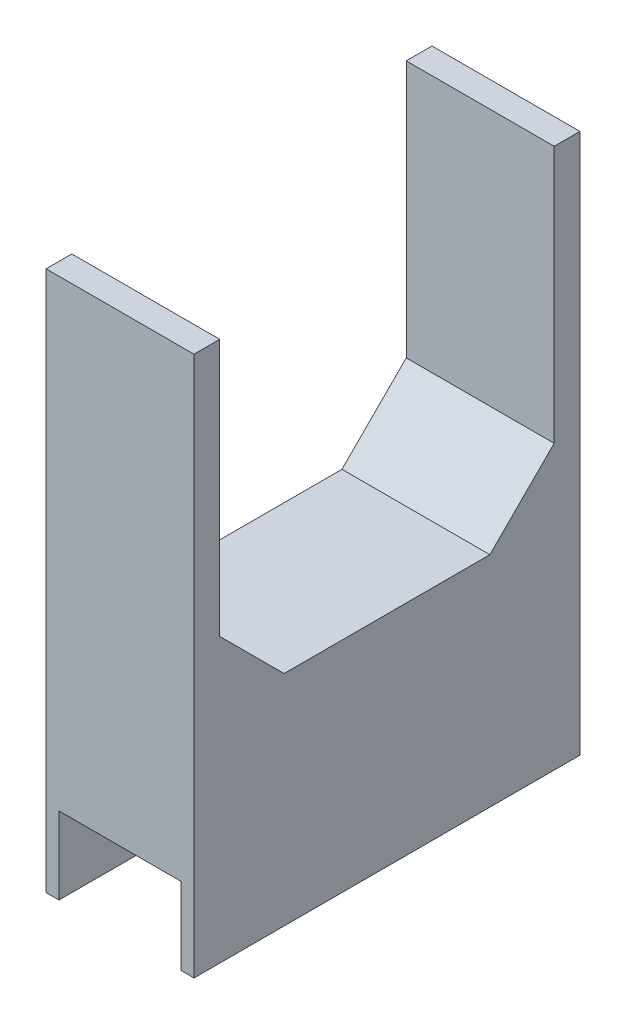
SolidWorks part; units mm, degrees
ref_plane "Front Plane" through (0, 0, 0) normal (0, 0, 1) x (1, 0, 0)
ref_plane "Top Plane" through (0, 0, 0) normal (0, 1, 0) x (1, 0, 0)
ref_plane "Right Plane" through (0, 0, 0) normal (1, 0, 0) x (0, 0, -1)
sketch "Sketch1" plane through (0, 0, 0) normal (0, 1, 0) x (1, 0, 0)
  line L1 (-5.75, -15) -> (5.75, -15)
  line L2 (-5.75, -15) -> (-5.75, 15)
  line L3 (-5.75, 15) -> (5.75, 15)
  line L4 (5.75, -15) -> (5.75, 15)
  line L5 (-5.75, -15) -> (5.75, 15) construction
  line L6 (-5.75, 15) -> (5.75, -15) construction
  point P0 (0, 0)
  dimension "D1" = 30
  dimension "D2" = 11.5
extrude "Boss-Extrude1" add sketch "Sketch1" along normal blind 11
sketch "Sketch3" plane through (0, 0, 0) normal (0, -1, 0) x (1, 0, 0)
  line L1 (-5.75, -15) -> (5.75, -15)
  line L2 (-5.75, -15) -> (-5.75, 15)
  line L3 (-5.75, 15) -> (5.75, 15)
  line L4 (5.75, -15) -> (5.75, 15)
  line L5 (-5.75, -15) -> (5.75, 15) construction
  line L6 (-5.75, 15) -> (5.75, -15) construction
  point P0 (0, 0)
extrude "Boss-Extrude3" add sketch "Sketch3" along normal blind 6
sketch "Sketch4" plane through (0, 0, 15) normal (0, 0, 1) x (1, 0, 0)
  line L0 (5.75, -6) -> (-5.75, -6) construction
  line L1 (-4.75, -6) -> (4.75, -6)
  line L2 (-4.75, -6) -> (-4.75, 0)
  line L3 (-4.75, 0) -> (4.75, 0)
  line L4 (4.75, -6) -> (4.75, 0)
  line L5 (-5.75, 11) -> (-5.75, -6) construction
  line L6 (5.75, 11) -> (5.75, -6) construction
  dimension "D1" = 1
  dimension "D2" = 1
  dimension "D3" = 6
extrude "Cut-Extrude1" cut sketch "Sketch4" against normal through all
sketch "Sketch7" plane through (0, 0, 0) normal (0, -1, 0) x (1, 0, 0)
  line L1 (-1, -3) -> (1, -3)
  line L2 (-1, -3) -> (-1, 3)
  line L3 (-1, 3) -> (1, 3)
  line L4 (1, -3) -> (1, 3)
  line L5 (-1, -3) -> (1, 3) construction
  line L6 (-1, 3) -> (1, -3) construction
  point P0 (0, 0)
  dimension "D1" = 2
  dimension "D2" = 6
extrude "Cut-Extrude2" cut sketch "Sketch7" against normal blind 10
sketch "Sketch8" plane through (0, 11, 0) normal (0, 1, 0) x (1, 0, 0)
  line L1 (-5.75, -15) -> (5.75, -15)
  line L2 (-5.75, -15) -> (-5.75, 15)
  line L3 (-5.75, 15) -> (5.75, 15)
  line L4 (5.75, -15) -> (5.75, 15)
  line L5 (-5.75, -15) -> (5.75, 15) construction
  line L6 (-5.75, 15) -> (5.75, -15) construction
  point P0 (0, 0)
extrude "Boss-Extrude4" add sketch "Sketch8" along normal blind 25
sketch "Sketch9" plane through (-5.75, 0, 0) normal (-1, 0, 0) x (0, 0, 1)
  line L0 (-15, 36) -> (15, 36) construction
  line L1 (-13, 36) -> (13, 36)
  line L2 (-13, 36) -> (-13, 11)
  line L3 (-13, 11) -> (13, 11)
  line L4 (13, 36) -> (13, 11)
  line L5 (-15, 36) -> (-15, -6) construction
  line L6 (15, 36) -> (15, -6) construction
  dimension "D1" = 2
  dimension "D2" = 2
  dimension "D3" = 25
extrude "Cut-Extrude3" cut sketch "Sketch9" against normal through all
chamfer "Chamfer1" distance 5 angle 45 2 edges at (0, 11, 13) (0, 11, -13)
